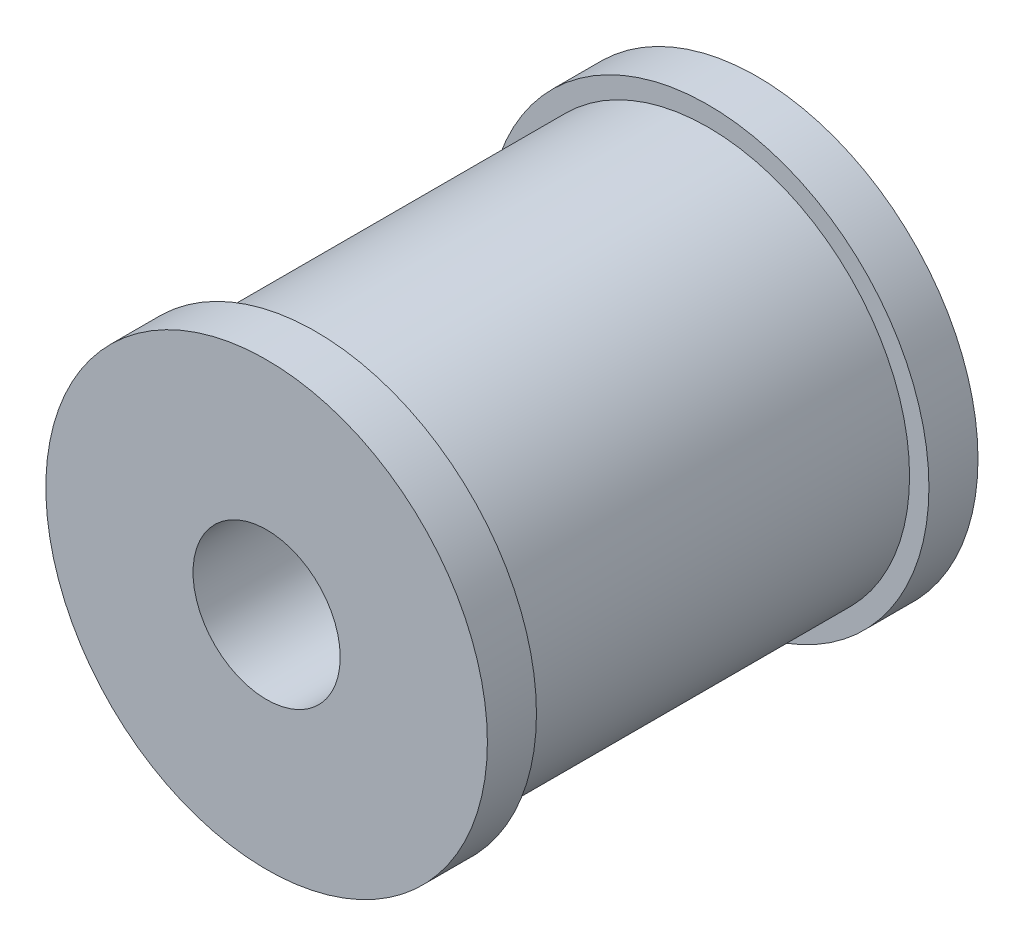
SolidWorks part; units mm, degrees
ref_plane "前视基准面" through (0, 0, 0) normal (0, 0, 1) x (1, 0, 0)
ref_plane "上视基准面" through (0, 0, 0) normal (0, 1, 0) x (1, 0, 0)
ref_plane "右视基准面" through (0, 0, 0) normal (1, 0, 0) x (0, 0, -1)
sketch "草图1" plane through (0, 0, 0) normal (0, 0, 1) x (1, 0, 0)
  circle A0 centre (0, 0) radius 3
  circle A1 centre (0, 0) radius 9
  dimension "D1" = 18
  dimension "D2" = 6
extrude "凸台-拉伸1" add sketch "草图1" along normal blind 20 contours A1
ref_plane "基准面1" through (0, 0, 10) normal (0, 0, 1) x (1, 0, 0)
sketch "草图3" plane through (0, 0, 10) normal (0, 0, 1) x (1, 0, 0)
  circle A0 centre (0, 0) radius 8.21
  dimension "D1" = 16.42
extrude "切除-拉伸-薄壁1" cut sketch "草图3" against normal blind 8 and the other way blind 8 thin
